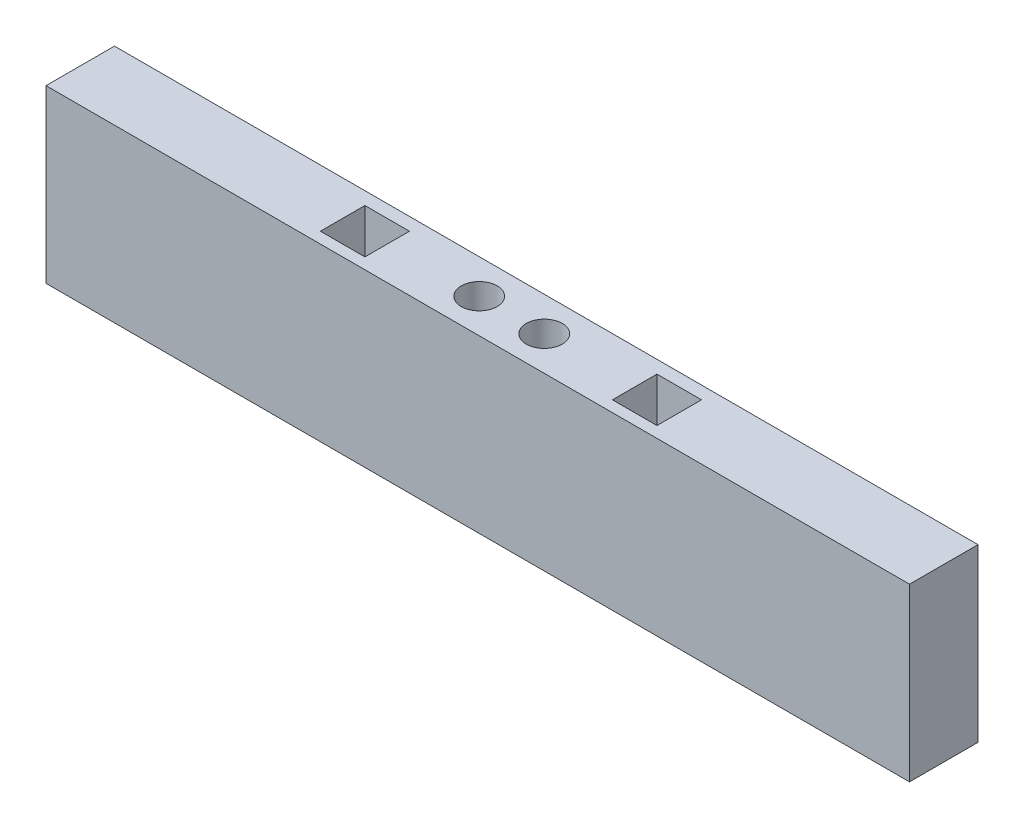
SolidWorks part; units mm, degrees
ref_plane "Front Plane" through (0, 0, 0) normal (0, 0, 1) x (1, 0, 0)
ref_plane "Top Plane" through (0, 0, 0) normal (0, 1, 0) x (1, 0, 0)
ref_plane "Right Plane" through (0, 0, 0) normal (1, 0, 0) x (0, 0, -1)
sketch "Sketch1" plane through (0, 0, 0) normal (0, 0, 1) x (1, 0, 0)
  line L1 (-107.8214, 92.0904) -> (-7.8214, 92.0904)
  line L3 (-107.8214, 44.0904) -> (-7.8214, 44.0904)
  line L5 (-107.8214, 92.0904) -> (-182.8214, 92.0904)
  line L7 (-107.8214, 44.0904) -> (-182.8214, 44.0904)
  line L8 (-182.8214, 92.0904) -> (-182.8214, 44.0904)
  line L9 (-7.8214, 92.0904) -> (117.1786, 92.0904)
  line L11 (-7.8214, 44.0904) -> (117.1786, 44.0904)
  line L12 (117.1786, 92.0904) -> (117.1786, 44.0904)
  dimension "D1" = 48
  dimension "D2" = 100
  dimension "D3" = 75
  dimension "D4" = 125
extrude "Boss-Extrude1" add sketch "Sketch1" along normal blind 20
sketch "Sketch5" plane through (0, 92.0904, 0) normal (0, 1, 0) x (1, 0, 0)
  line L0 (-182.8214, -20) -> (-157.8214, -20) construction
  line L2 (117.1786, -20) -> (-182.8214, -20) construction
  line L3 (-157.8214, -20) -> (-57.8214, -20) construction
  line L4 (-57.8214, -20) -> (-66.3214, -20) construction
  line L5 (-66.3214, -20) -> (-66.3214, -16) construction
  line L6 (-66.3214, -16) -> (-66.3214, -10) construction
  line L7 (-66.3214, -10) -> (-47.3214, -10) construction
  circle A0 centre (-66.3214, -10) radius 5.25
  circle A1 centre (-47.3214, -10) radius 5.25
extrude "Cut-Extrude4" cut sketch "Sketch5" against normal blind 20
sketch "Sketch6" plane through (0, 92.0904, 0) normal (0, 1, 0) x (1, 0, 0)
  line L0 (-182.8214, 0) -> (-105.6914, 0) construction
  line L1 (117.1786, 0) -> (-182.8214, 0) construction
  line L2 (-105.6914, 0) -> (-105.6914, -4) construction
  line L3 (-105.9414, -3.75) -> (-92.9414, -3.75)
  line L8 (-92.9414, -3.75) -> (-92.9414, -16.75)
  line L9 (-105.9414, -16.75) -> (-92.9414, -16.75)
  line L10 (-105.9414, -3.75) -> (-105.9414, -16.75)
extrude "Cut-Extrude5" cut sketch "Sketch6" against normal blind 15.5
sketch "Sketch7" plane through (0, 92.0904, 0) normal (0, 1, 0) x (1, 0, 0)
  line L0 (117.1786, 0) -> (-7.9138, 0) construction
  line L1 (117.1786, 0) -> (-182.8214, 0) construction
  line L2 (-7.9138, 0) -> (-7.9138, -4) construction
  line L3 (-7.6638, -3.75) -> (-20.6638, -3.75)
  line L8 (-20.6638, -3.75) -> (-20.6638, -16.75)
  line L9 (-7.6638, -16.75) -> (-20.6638, -16.75)
  line L10 (-7.6638, -3.75) -> (-7.6638, -16.75)
extrude "Cut-Extrude6" cut sketch "Sketch7" against normal blind 15.5
sketch "Sketch8" plane through (0, 0, 20) normal (0, 0, 1) x (1, 0, 0)
  line L0 (117.1786, 44.0904) -> (117.1786, 92.0904) construction
  line L1 (-182.8214, 44.0904) -> (117.1786, 44.0904)
  line L2 (-182.8214, 44.0904) -> (-182.8214, -57.9096)
  line L3 (-182.8214, -57.9096) -> (117.1786, -57.9096)
  line L4 (117.1786, 44.0904) -> (117.1786, -57.9096)
  dimension "D1" = 150
extrude "Boss-Extrude2" add sketch "Sketch8" against normal up to surface (20 mm away) up to face at (-32.8214, 68.0904, 0)
sketch "Sketch9" plane through (0, 92.0904, 0) normal (0, 1, 0) x (1, 0, 0)
  line L1 (-105.9414, -3.75) -> (-105.9414, -16.75) construction
  line L2 (-7.6638, -3.75) -> (-7.6638, -16.75) construction
  line L4 (117.1786, 0) -> (-182.8214, 0) construction
  line L5 (69.3362, 0) -> (69.3362, -20) construction
  line L6 (117.1786, -20) -> (-182.8214, -20) construction
  line L8 (117.1786, -20) -> (69.3362, -20)
  line L9 (117.1786, -20) -> (117.1786, 0)
  line L10 (117.1786, 0) -> (69.3362, 0)
  line L11 (69.3362, -20) -> (69.3362, 0)
  dimension "D1" = 77
extrude "Cut-Extrude7" cut sketch "Sketch9" against normal up to vertex
sketch "Sketch10" plane through (0, 0, 0) normal (0, 0, -1) x (-1, 0, 0)
  line L3 (-69.3362, -7.9096) -> (182.8214, -7.9096)
  line L6 (182.8214, 92.0904) -> (182.8214, -57.9096) construction
  line L8 (-69.3362, -57.9096) -> (182.8214, -57.9096)
  line L9 (-69.3362, -57.9096) -> (-69.3362, -7.9096)
  line L11 (182.8214, -57.9096) -> (182.8214, -7.9096)
  dimension "D1" = 50
extrude "Cut-Extrude8" cut sketch "Sketch10" against normal blind 310
sketch "Sketch11" plane through (0, 0, 0) normal (0, 0, -1) x (-1, 0, 0)
  line L1 (-69.3362, -7.9096) -> (182.8214, -7.9096)
  line L2 (-69.3362, -7.9096) -> (-69.3362, 42.0904)
  line L3 (-69.3362, 42.0904) -> (182.8214, 42.0904)
  line L4 (182.8214, -7.9096) -> (182.8214, 42.0904)
extrude "Cut-Extrude9" cut sketch "Sketch11" against normal up to surface (20 mm away) up to face at (-56.7426, 42.0904, 20)
